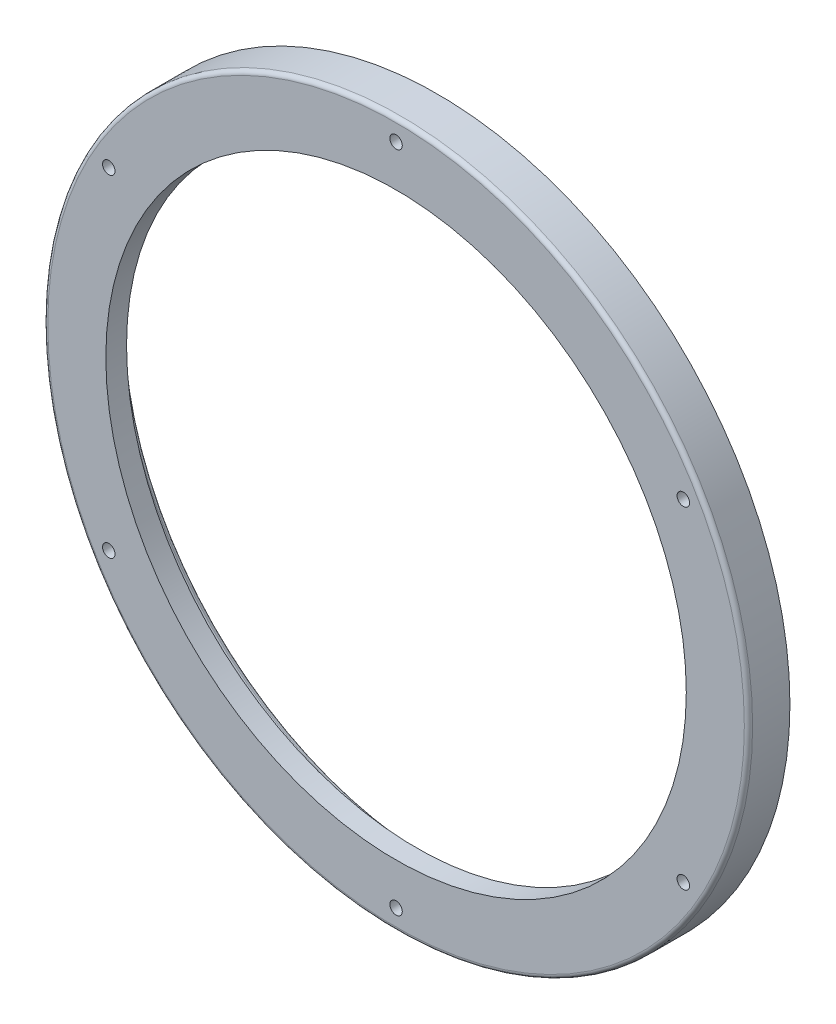
SolidWorks part; units mm, degrees
ref_plane "Ön Düzlem" through (0, 0, 0) normal (0, 0, 1) x (1, 0, 0)
ref_plane "Üst Düzlem" through (0, 0, 0) normal (0, 1, 0) x (1, 0, 0)
ref_plane "Sağ Düzlem" through (0, 0, 0) normal (1, 0, 0) x (0, 0, -1)
sketch "Sketch1" plane through (0, 0, 0) normal (0, 0, 1) x (1, 0, 0)
  circle A0 centre (0, 0) radius 85
  circle A1 centre (0, 0) radius 70
  dimension "D1" = 170
  dimension "D2" = 140
extrude "Boss-Extrude1" add sketch "Sketch1" along normal blind 10
sketch "Sketch2" plane through (0, 0, 0) normal (0, 0, 1) x (1, 0, 0)
  circle A0 centre (0, 0) radius 75
  dimension "D1" = 150
extrude "Cut-Extrude2" cut sketch "Sketch2" along normal blind 5
sketch "Sketch3" plane through (0, 0, 0) normal (0, 0, -1) x (-1, 0, 0)
  line L0 (0, 85) -> (0, 75) construction
  circle A0 centre (0, 0) radius 85 construction
  circle A1 centre (0, 0) radius 75 construction
  circle A2 centre (0, 80) radius 1.5
  dimension "D1" = 3
extrude "Cut-Extrude3" cut sketch "Sketch3" against normal up to surface (10 mm away) up to face at (85, 0, 10)
pattern_circular "CirPattern1" count 6 over 360 about axis through (0, 0, 0) along (0, 0, 1) of "Cut-Extrude3"
fillet "Fillet1" radius 1 2 edges at (85, 0, 10) (75, 0, 0)
